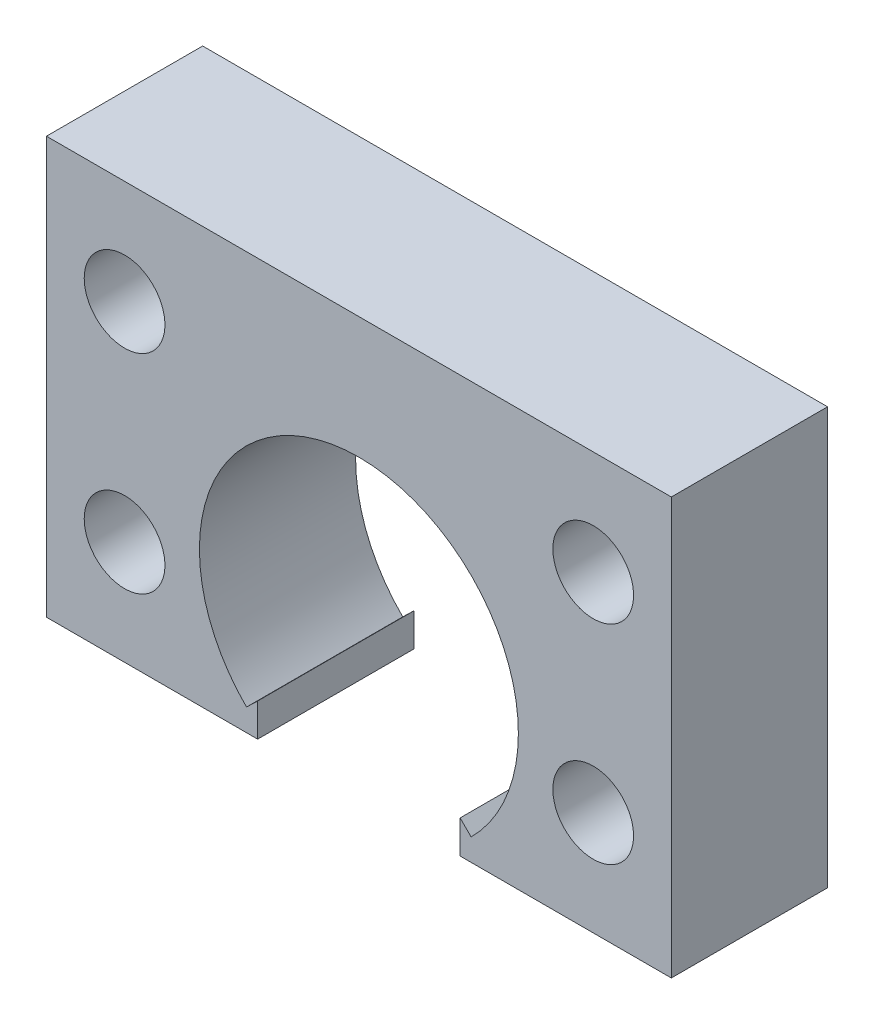
SolidWorks part; units mm, degrees
ref_plane "Płaszczyzna przednia" through (0, 0, 0) normal (0, 0, 1) x (1, 0, 0)
ref_plane "Płaszczyzna górna" through (0, 0, 0) normal (0, 1, 0) x (1, 0, 0)
ref_plane "Płaszczyzna prawa" through (0, 0, 0) normal (1, 0, 0) x (0, 0, -1)
sketch "Szkic1" plane through (0, 0, 0) normal (0, 0, 1) x (1, 0, 0)
  line L0 (59.503, 0) -> (35.503, 0)
  line L1 (59.503, 0) -> (59.503, -16)
  line L2 (35.503, 0) -> (35.503, -16)
  line L3 (59.503, -16) -> (35.503, -16)
  dimension "D1" = 24
  dimension "D2" = 16
extrude "Dodanie-wyciągnięcie1" add sketch "Szkic1" against normal blind 6
sketch "Szkic2" plane through (0, 0, -6) normal (0, 0, 1) x (1, 0, 0)
  line L0 (35.503, -16) -> (59.503, -16) construction
  line L1 (35.503, 0) -> (35.503, -16) construction
  line L2 (43.6145, -16) -> (43.6145, -14.7305)
  line L3 (35.503, -16) -> (59.503, -16) construction
  line L5 (51.3914, -16) -> (51.3914, -14.7305)
  line L6 (51.3914, -14.7305) -> (51.8128, -15.1521)
  line L7 (51.3914, -16) -> (43.6145, -16)
  line L9 (43.6145, -14.7305) -> (43.1868, -15.1458)
  arc A0 (51.9218, -15.0415) -> (43.0842, -15.0415) centre (47.503, -10.8) ccw
  arc A1 (51.9218, -15.0415) -> (51.8128, -15.1521) centre (47.503, -10.8) cw
  arc A2 (43.0842, -15.0415) -> (43.1868, -15.1458) centre (47.503, -10.8) ccw
  dimension "D1" = 5.2
  dimension "D2" = 12.25
  dimension "D3" = 12
  dimension "D4" = 3.8884
  dimension "D5" = 3.8884
  dimension "D6" = 0
extrude "Wytnij-wyciągnięcie1" cut sketch "Szkic2" along normal blind 6
sketch "Szkic3" plane through (0, 0, -6) normal (0, 0, -1) x (-1, 0, 0)
  circle A5 centre (-56.503, -12) radius 1.55 construction
  circle A6 centre (-56.503, -4) radius 1.55 construction
  circle A7 centre (-38.503, -4) radius 1.55 construction
  circle A8 centre (-38.503, -12) radius 1.55 construction
  circle A9 centre (-56.503, -12) radius 1.55
  circle A10 centre (-56.503, -4) radius 1.55
  circle A11 centre (-38.503, -4) radius 1.55
  circle A12 centre (-38.503, -12) radius 1.55
extrude "Wytnij-wyciągnięcie2" cut sketch "Szkic3" against normal through all
equation "\"tolerancja_wpusy\"=0.2"
equation "\"dlugosc_wpustu_duzy\"=20"
equation "\"srednica_otworu_M3\"=3.1"
equation "\"szerokosc_nogi_T\"=3.1"
equation "\"dlugosc_T_30\"=11"
equation "\"grubosc_na_nakretke_kwadrat\"=2"
equation "\"szerokosc_na_nakretke_kwadrat\"=5.85"
equation "\"wyokosc_nadstawki_T\"=0.5"
equation "\"dlugosc_T_20_6\"=14"
